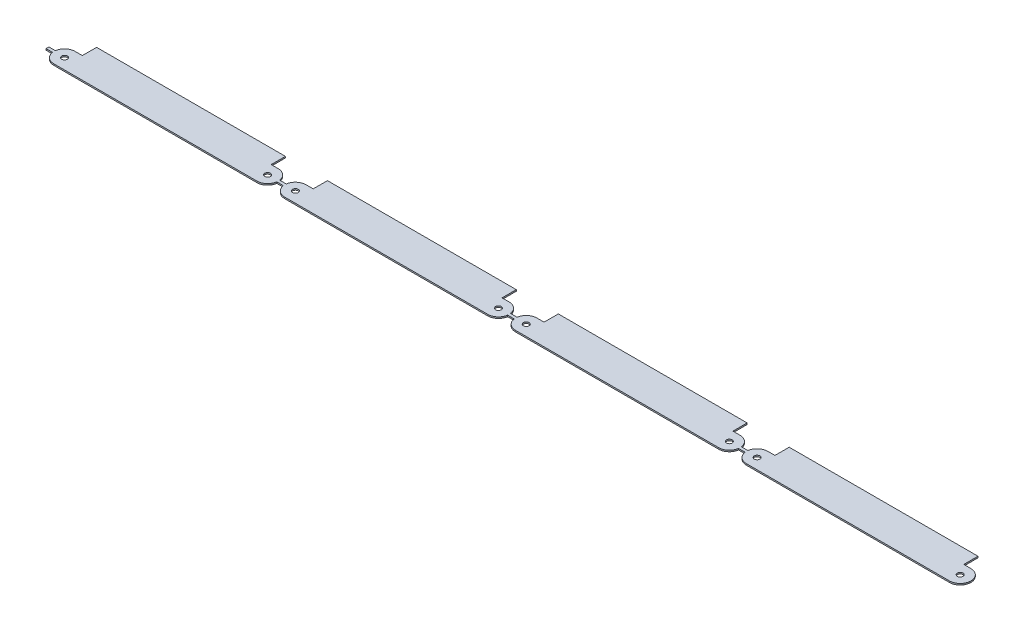
SolidWorks part; units mm, degrees
ref_plane "Front Plane" through (0, 0, 0) normal (0, 0, 1) x (1, 0, 0)
ref_plane "Top Plane" through (0, 0, 0) normal (0, 1, 0) x (1, 0, 0)
ref_plane "Right Plane" through (0, 0, 0) normal (1, 0, 0) x (0, 0, -1)
sketch "Sketch1" plane through (0, 0, 0) normal (0, 1, 0) x (1, 0, 0)
  line L0 (0, 0) -> (142.5, 0) construction
  line L1 (0, 7.5) -> (5, 7.5)
  line L2 (0, 7.5) -> (142.5, 7.5) construction
  line L3 (0, 7.5) -> (0, -7.5) construction
  line L4 (0, -7.5) -> (142.5, -7.5)
  line L5 (142.5, 7.5) -> (142.5, -7.5) construction
  line L6 (0, 7.5) -> (142.5, -7.5) construction
  line L7 (0, -7.5) -> (142.5, 7.5) construction
  line L8 (5, 7.5) -> (5, 17.5)
  line L9 (5, 17.5) -> (137.5, 17.5)
  line L10 (137.5, 17.5) -> (137.5, 7.5)
  line L11 (137.5, 7.5) -> (142.5, 7.5)
  line L12 (71.25, 0) -> (71.25, 17.5) construction
  line L13 (149.933, 1) -> (150, 1)
  line L14 (150, 1) -> (150, -1)
  line L15 (150, -1) -> (149.933, -1)
  line L16 (149.997, -1) -> (154.567, -1)
  line L17 (142.5, 0) -> (150, 0) construction
  line L18 (149.997, 1) -> (154.567, 1)
  line L19 (162, -7.5) -> (304.5, -7.5)
  line L20 (162, 7.5) -> (167, 7.5)
  line L21 (167, 7.5) -> (167, 17.5)
  line L27 (167, 17.5) -> (299.5, 17.5)
  line L28 (299.5, 7.5) -> (304.5, 7.5)
  line L29 (299.5, 17.5) -> (299.5, 7.5)
  line L31 (-7.5, 0) -> (-12.003, 0) construction
  line L32 (-12.003, 1) -> (-12.003, -1)
  line L33 (-12.003, -1) -> (-7.433, -1)
  line L39 (312, -1) -> (311.933, -1)
  line L40 (311.933, 1) -> (312, 1)
  line L41 (312, 1) -> (312, -1)
  line L44 (-12.003, 1) -> (-7.433, 1)
  line L45 (311.997, -1) -> (316.567, -1)
  line L46 (311.997, 1) -> (316.567, 1)
  line L47 (324, -7.5) -> (466.5, -7.5)
  line L48 (324, 7.5) -> (329, 7.5)
  line L49 (329, 7.5) -> (329, 17.5)
  line L50 (329, 17.5) -> (461.5, 17.5)
  line L51 (461.5, 7.5) -> (466.5, 7.5)
  line L52 (461.5, 17.5) -> (461.5, 7.5)
  line L53 (474, -1) -> (473.933, -1)
  line L54 (473.933, 1) -> (474, 1)
  line L55 (474, 1) -> (474, -1)
  line L56 (473.997, -1) -> (478.567, -1)
  line L57 (473.997, 1) -> (478.567, 1)
  line L58 (486, -7.5) -> (628.5, -7.5)
  line L59 (486, 7.5) -> (491, 7.5)
  line L60 (491, 7.5) -> (491, 17.5)
  line L61 (491, 17.5) -> (623.5, 17.5)
  line L62 (623.5, 7.5) -> (628.5, 7.5)
  line L63 (623.5, 17.5) -> (623.5, 7.5)
  line L64 (636, -1) -> (635.933, -1)
  line L65 (635.933, 1) -> (636, 1)
  line L66 (636, 1) -> (636, -1)
  circle A0 centre (0, 0) radius 2
  circle A1 centre (142.5, 0) radius 2
  arc A2 (0, 7.5) -> (0, -7.5) centre (0, 0) ccw construction
  arc A3 (142.5, -7.5) -> (142.5, 7.5) centre (142.5, 0) ccw construction
  arc A5 (142.5, 7.5) -> (149.933, 1) centre (142.5, 0) cw
  arc A7 (149.933, -1) -> (142.5, -7.5) centre (142.5, 0) cw
  arc A8 (-7.433, 1) -> (0, 7.5) centre (0, 0) cw
  arc A9 (-7.433, -1) -> (0, -7.5) centre (0, 0) ccw
  arc A10 (154.567, 1) -> (162, 7.5) centre (162, 0) cw
  arc A11 (154.567, -1) -> (162, -7.5) centre (162, 0) ccw
  arc A12 (311.933, -1) -> (304.5, -7.5) centre (304.5, 0) cw
  arc A13 (304.5, 7.5) -> (311.933, 1) centre (304.5, 0) cw
  arc A14 (316.567, 1) -> (324, 7.5) centre (324, 0) cw
  arc A15 (316.567, -1) -> (324, -7.5) centre (324, 0) ccw
  arc A16 (473.933, -1) -> (466.5, -7.5) centre (466.5, 0) cw
  arc A17 (466.5, 7.5) -> (473.933, 1) centre (466.5, 0) cw
  arc A18 (478.567, 1) -> (486, 7.5) centre (486, 0) cw
  arc A19 (478.567, -1) -> (486, -7.5) centre (486, 0) ccw
  arc A20 (635.933, -1) -> (628.5, -7.5) centre (628.5, 0) cw
  arc A21 (628.5, 7.5) -> (635.933, 1) centre (628.5, 0) cw
  circle A22 centre (162, 0) radius 2
  circle A23 centre (304.5, 0) radius 2
  circle A24 centre (324, 0) radius 2
  circle A25 centre (466.5, 0) radius 2
  circle A26 centre (486, 0) radius 2
  circle A27 centre (628.5, 0) radius 2
  point P5 (71.25, 0)
  dimension "D3" = 10
  dimension "D6" = 4
  dimension "D8" = 162.003
  dimension "D2" = 15
  dimension "D4" = 150
  dimension "D5" = 5
  dimension "D7" = 2
  dimension "D9" = 4
  dimension "D12" = 4.57
  dimension "D13" = 2
  dimension "D10" = 162
extrude "Boss-Extrude1" add sketch "Sketch1" along normal blind 1
